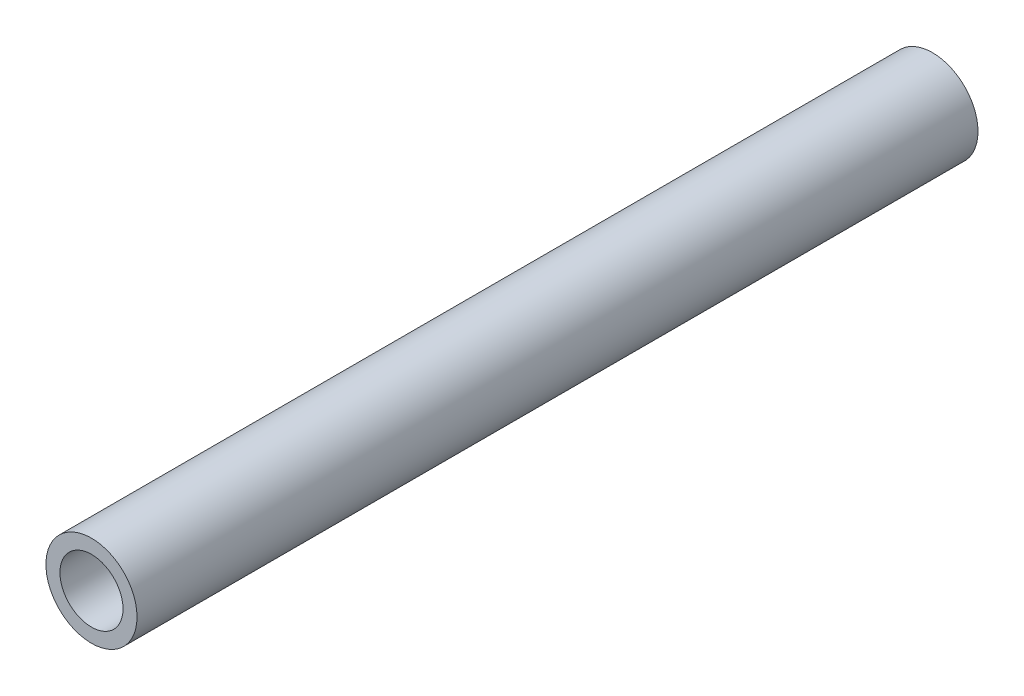
SolidWorks part; units mm, degrees
material "AISI 304"
ref_plane "前视基准面" through (0, 0, 0) normal (0, 0, 1) x (1, 0, 0)
ref_plane "上视基准面" through (0, 0, 0) normal (0, 1, 0) x (1, 0, 0)
ref_plane "右视基准面" through (0, 0, 0) normal (1, 0, 0) x (0, 0, -1)
sketch "Sketch1" plane through (0, 0, 0) normal (0, 0, 1) x (1, 0, 0)
  circle A0 centre (0, 0) radius 4.5
  circle A1 centre (0, 0) radius 6.5
  dimension "D1" = 9
  dimension "D2" = 13
extrude "Boss-Extrude1" add sketch "Sketch1" along normal blind 120
